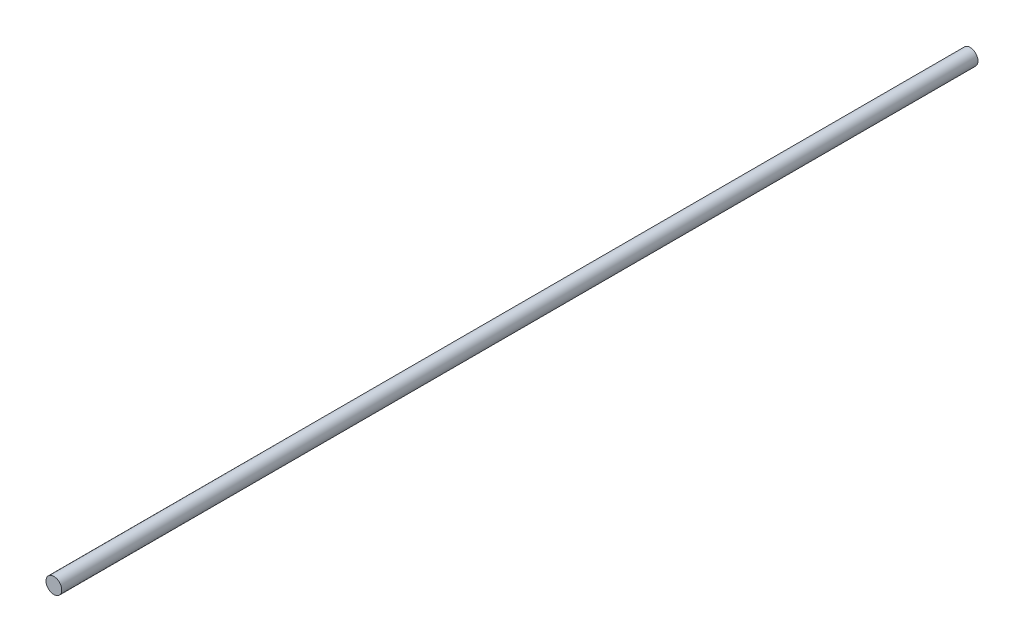
SolidWorks part; units mm, degrees
ref_plane "Front Plane" through (0, 0, 0) normal (0, 0, 1) x (1, 0, 0)
ref_plane "Top Plane" through (0, 0, 0) normal (0, 1, 0) x (1, 0, 0)
ref_plane "Right Plane" through (0, 0, 0) normal (1, 0, 0) x (0, 0, -1)
sketch "Sketch1" plane through (0, 0, 0) normal (0, 0, 1) x (1, 0, 0)
  circle A0 centre (0, 0) radius 4
  dimension "D1" = 8
extrude "Boss-Extrude1" add sketch "Sketch1" along normal blind 465
cosmetic thread "Cosmetic Thread1" parameters "D2"=6.891
